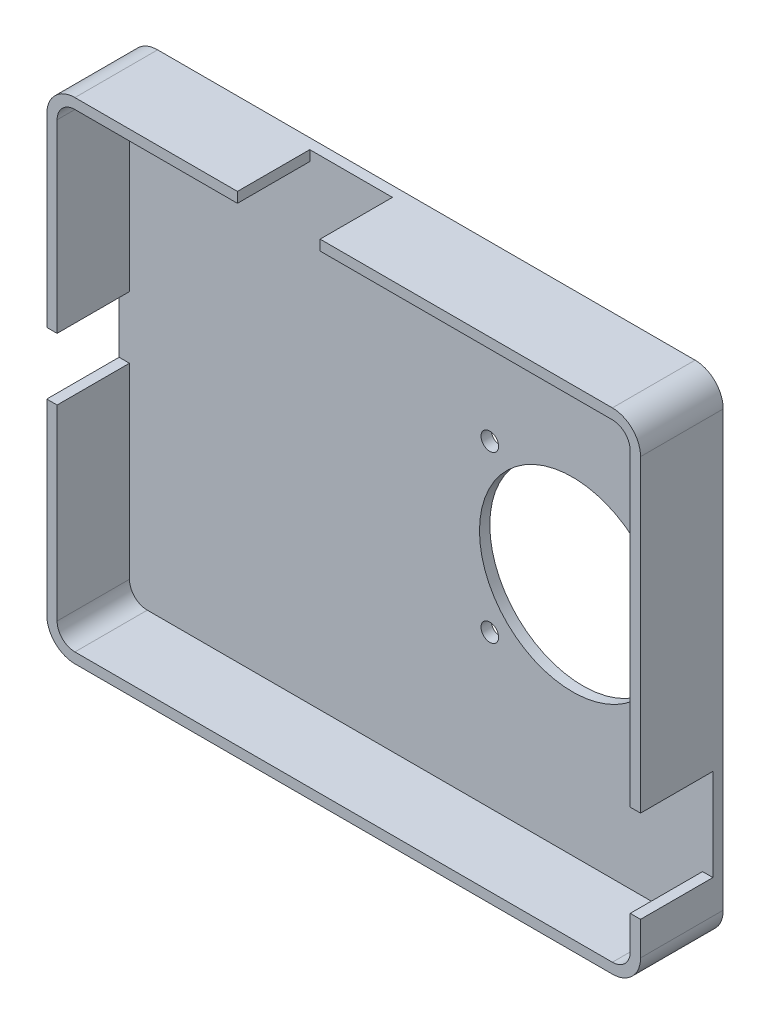
SolidWorks part; units mm, degrees
ref_plane "Front Plane" through (0, 0, 0) normal (0, 0, 1) x (1, 0, 0)
ref_plane "Top Plane" through (0, 0, 0) normal (0, 1, 0) x (1, 0, 0)
ref_plane "Right Plane" through (0, 0, 0) normal (1, 0, 0) x (0, 0, -1)
sketch "Sketch1" plane through (0, 0, 0) normal (0, 0, 1) x (1, 0, 0)
  line L0 (52, 45.45) -> (-52, 45.45)
  line L1 (-55.45, 42) -> (-55.45, -42)
  line L2 (-52, -45.45) -> (52, -45.45)
  line L3 (55.45, -42) -> (55.45, 42)
  line L4 (52, 47.45) -> (-52, 47.45)
  line L5 (-57.45, 42) -> (-57.45, -42)
  line L6 (-52, -47.45) -> (52, -47.45)
  line L7 (57.45, -42) -> (57.45, 42)
  line L28 (52, 45) -> (-52, 45) construction
  line L29 (55, -42) -> (55, 42) construction
  line L30 (-52, -45) -> (52, -45) construction
  line L31 (-55, 42) -> (-55, -42) construction
  arc A0 (-52, 45.45) -> (-55.45, 42) centre (-52, 42) ccw
  arc A1 (-55.45, -42) -> (-52, -45.45) centre (-52, -42) ccw
  arc A2 (52, -45.45) -> (55.45, -42) centre (52, -42) ccw
  arc A3 (55.45, 42) -> (52, 45.45) centre (52, 42) ccw
  arc A4 (-52, 47.45) -> (-57.45, 42) centre (-52, 42) ccw
  arc A5 (-57.45, -42) -> (-52, -47.45) centre (-52, -42) ccw
  arc A6 (52, -47.45) -> (57.45, -42) centre (52, -42) ccw
  arc A7 (57.45, 42) -> (52, 47.45) centre (52, 42) ccw
  arc A24 (-52, 45) -> (-55, 42) centre (-52, 42) ccw construction
  arc A25 (55, 42) -> (52, 45) centre (52, 42) ccw construction
  arc A26 (52, -45) -> (55, -42) centre (52, -42) ccw construction
  arc A27 (-55, -42) -> (-52, -45) centre (-52, -42) ccw construction
  dimension "D1" = 0.45
  dimension "D2" = 2
extrude "Boss-Extrude1" add sketch "Sketch1" along normal blind 14
sketch "Sketch2" plane through (0, 0, 0) normal (0, 0, -1) x (-1, 0, 0)
  line L4 (-57.45, 42) -> (-57.45, -42)
  line L5 (-52, -47.45) -> (52, -47.45)
  line L6 (57.45, -42) -> (57.45, 42)
  line L7 (52, 47.45) -> (-52, 47.45)
  line L8 (-57.45, 42) -> (-57.45, -42)
  line L9 (-52, -47.45) -> (52, -47.45)
  line L10 (57.45, -42) -> (57.45, 42)
  line L11 (52, 47.45) -> (-52, 47.45)
  arc A4 (-52, 47.45) -> (-57.45, 42) centre (-52, 42) ccw
  arc A5 (-57.45, -42) -> (-52, -47.45) centre (-52, -42) ccw
  arc A6 (52, -47.45) -> (57.45, -42) centre (52, -42) ccw
  arc A7 (57.45, 42) -> (52, 47.45) centre (52, 42) ccw
  arc A8 (-52, 47.45) -> (-57.45, 42) centre (-52, 42) ccw
  arc A9 (-57.45, -42) -> (-52, -47.45) centre (-52, -42) ccw
  arc A10 (52, -47.45) -> (57.45, -42) centre (52, -42) ccw
  arc A11 (57.45, 42) -> (52, 47.45) centre (52, 42) ccw
  dimension "D1" = 0
extrude "Boss-Extrude2" add sketch "Sketch2" along normal blind 2
sketch "Sketch4" plane through (0, 0, 0) normal (0, 0, 1) x (1, 0, 0)
  line L28 (-55.45, 6.2054) -> (-55.45, -5.7946)
  line L44 (-4.5544, 47.45) -> (-4.5544, 45.9)
  line L45 (55.45, -17.7402) -> (55.4456, -35.5349)
  line L46 (-20.5544, 47.45) -> (-20.5544, 45.45)
  line L47 (-57.45, 6.2054) -> (-55.45, 6.2054)
  line L48 (-57.45, -5.7946) -> (-55.45, -5.7946)
  line L49 (55.4456, -35.5349) -> (56.4456, -35.5349)
  line L50 (57.45, -17.7402) -> (55.45, -17.7402)
  line L51 (55.4456, -35.5349) -> (57.45, -35.5349)
  line L52 (-20.5544, 45.45) -> (-4.5544, 45.45)
  line L53 (-4.5544, 45.45) -> (-4.5544, 47.45)
  line L54 (57.45, -35.5349) -> (57.45, -17.7402)
  line L55 (-52, 47.45) -> (52, 47.45) construction
  line L57 (-20.5544, 47.45) -> (-4.5544, 47.45)
  line L58 (52, 45.45) -> (-52, 45.45) construction
  line L59 (-55.45, 42) -> (-55.45, -42) construction
  line L61 (-57.45, 6.2054) -> (-57.45, -5.7946)
  line L62 (57.45, -42) -> (57.45, 42) construction
  line M22 (52, 45.45) -> (-52, 45.45)
  line M24 (-55.45, 42) -> (-55.45, -42)
  dimension "D1" = 2
extrude "Cut-Extrude1" cut sketch "Sketch4" along normal blind 94 contours L57 L46 L53 L44 M22 | L47 L61 L48 M24 | L51 L54 L50 L45
sketch "Sketch5" plane through (0, 0, -2) normal (0, 0, -1) x (-1, 0, 0)
  line L0 (0, 0) -> (-30.2815, 0) construction
  line L2 (-46.2815, -16) -> (-14.2815, -16) construction
  line L3 (-46.2815, -16) -> (-46.2815, 16) construction
  line L4 (-46.2815, 16) -> (-14.2815, 16) construction
  line L5 (-14.2815, -16) -> (-14.2815, 16) construction
  line L6 (-46.2815, -16) -> (-14.2815, 16) construction
  line L7 (-46.2815, 16) -> (-14.2815, -16) construction
  circle A0 centre (-14.2815, 16) radius 1.7
  circle A1 centre (-46.2815, 16) radius 1.7
  circle A2 centre (-46.2815, -16) radius 1.7
  circle A3 centre (-14.2815, -16) radius 1.7
  circle A4 centre (-30.2815, 0) radius 18
  dimension "D1" = 36
extrude "Cut-Extrude2" cut sketch "Sketch5" against normal blind 10
sketch "Sketch6" plane through (0, 0, -2) normal (0, 0, -1) x (-1, 0, 0)
  line L0 (0, 0) -> (57.45, 0) construction
  line L1 (57.45, -42) -> (57.45, 42) construction
  line L2 (10.5437, 17.7345) -> (49.8035, 17.7345)
  line L3 (49.8035, 17.7345) -> (30.1736, -16.2655)
  line L4 (30.1736, -16.2655) -> (10.5437, 17.7345)
  line L5 (17.0427, -16.2655) -> (23.1463, -5.6938)
  line L6 (-2.5872, 17.7345) -> (17.0427, -16.2655)
  line L7 (36.6726, 17.7345) -> (10.5437, 17.7345)
  line L8 (4.341, 13.7345) -> (17.0427, -8.2655)
  line L9 (17.0427, -8.2655) -> (20.8369, -1.6938)
  line L10 (29.7444, 13.7345) -> (17.4719, 13.7345)
  line L11 (42.8753, 13.7345) -> (30.1736, -8.2655)
  line L12 (30.1736, -8.2655) -> (17.4719, 13.7345)
  line L13 (17.4719, 13.7345) -> (42.8753, 13.7345)
  line L14 (9.6199, 17.7345) -> (11.9293, 13.7345)
  line L15 (20.8369, -1.6938) -> (23.1463, -5.6938)
  line L16 (24.07, 3.9062) -> (26.3794, -0.0938)
  line L17 (29.2825, 12.9345) -> (33.9013, 12.9345)
  line L18 (11.9293, 13.7345) -> (4.341, 13.7345)
  line L19 (9.6199, 17.7345) -> (-2.5872, 17.7345)
  line L20 (26.3794, -0.0938) -> (33.9013, 12.9345)
  line L21 (24.07, 3.9062) -> (29.2825, 12.9345)
extrude "Cut-Extrude3" cut sketch "Sketch6" against normal blind 1 contours L0 L4 L3 L11 L12 | L16 L0 L20 L17 L21 | L6 L0 L8 L18 L14 L19 | L0 L6 L5 L15 L9 L8 | L4 L0 L12 L10 L13 L11 L3 L2
